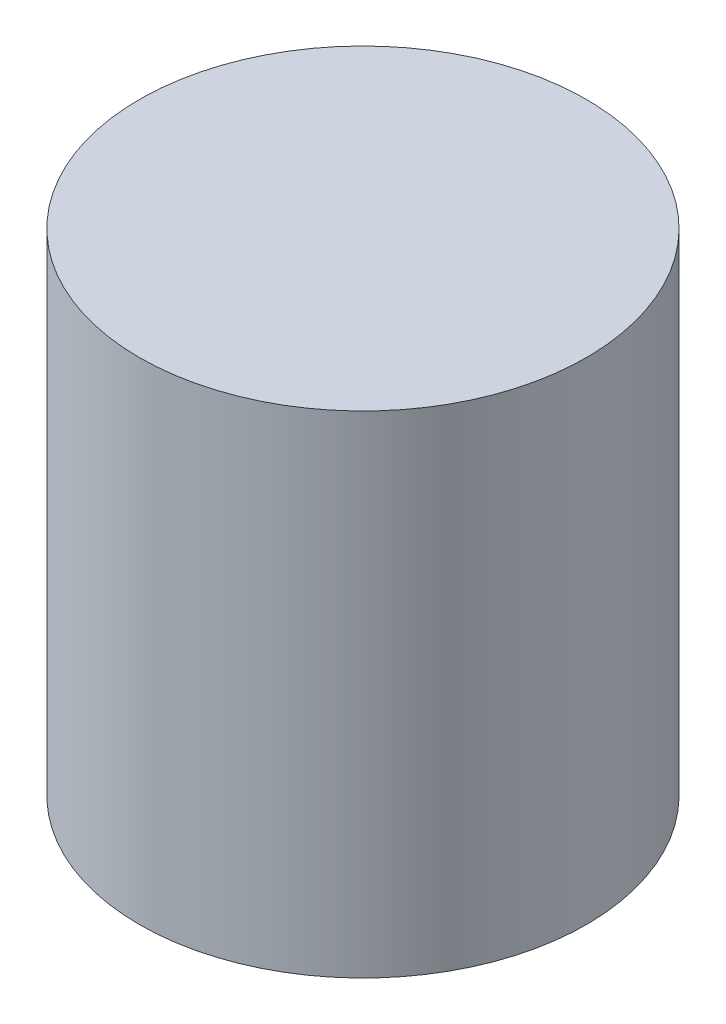
SolidWorks part; units mm, degrees
ref_plane "Front Plane" through (0, 0, 0) normal (0, 0, 1) x (1, 0, 0)
ref_plane "Top Plane" through (0, 0, 0) normal (0, 1, 0) x (1, 0, 0)
ref_plane "Right Plane" through (0, 0, 0) normal (1, 0, 0) x (0, 0, -1)
sketch "Sketch2" plane through (0, 0, 0) normal (0, 1, 0) x (1, 0, 0)
  circle A0 centre (-33.8409, 9.8136) radius 1.27
extrude "Boss-Extrude1" add sketch "Sketch2" along normal blind 2.79
sketch "Sketch3" plane through (0, 0, 0) normal (0, -1, 0) x (1, 0, 0)
  circle A0 centre (-33.8409, -9.8136) radius 1
extrude "Cut-Extrude1" cut sketch "Sketch3" against normal blind 1.5
